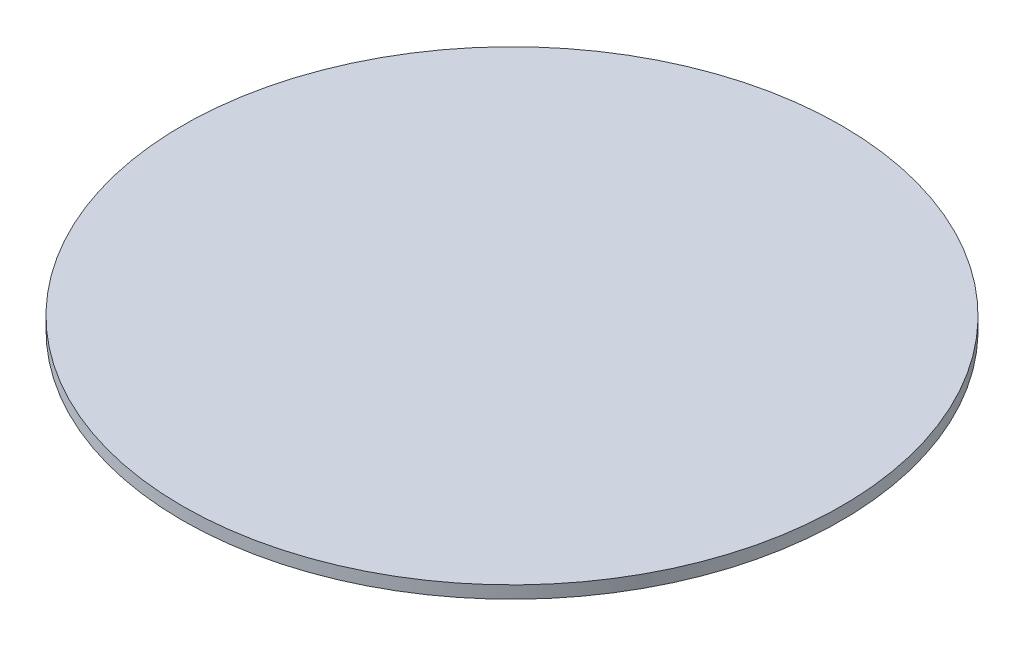
SolidWorks part; units mm, degrees
material "Oak"
ref_plane "Front Plane" through (0, 0, 0) normal (0, 0, 1) x (1, 0, 0)
ref_plane "Top Plane" through (0, 0, 0) normal (0, 1, 0) x (1, 0, 0)
ref_plane "Right Plane" through (0, 0, 0) normal (1, 0, 0) x (0, 0, -1)
sketch "Sketch1" plane through (0, 0, 0) normal (0, 1, 0) x (1, 0, 0)
  circle A0 centre (0, 0) radius 158.75
  dimension "D1" = 317.5
extrude "Boss-Extrude1" add sketch "Sketch1" along normal blind 6
sketch "Sketch2" plane through (0, 6, 0) normal (0, 1, 0) x (1, 0, 0)
  circle A0 centre (0, 0) radius 149.86
  dimension "D1" = 299.72
equation "\"D1@Sketch1\"=12.5in"
equation "\"D1@Sketch2\"=11.8in"
